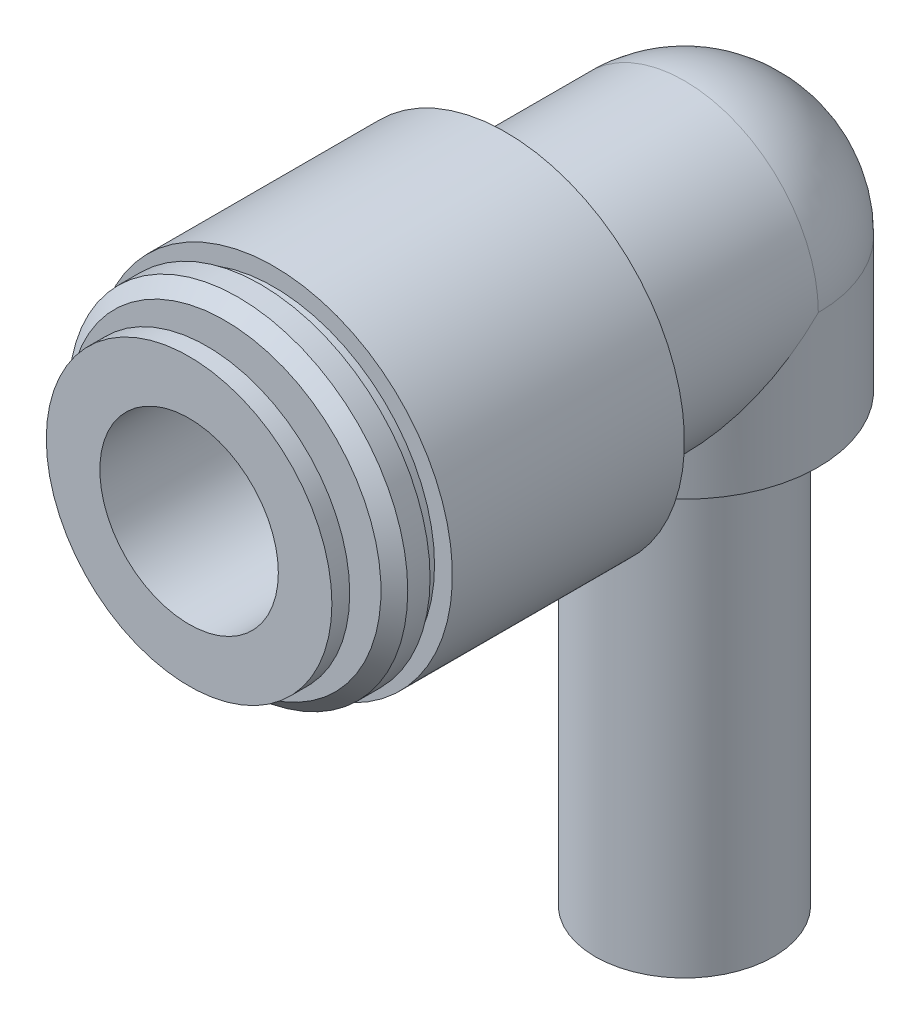
SolidWorks part; units mm, degrees
ref_plane "Спереди" through (0, 0, 0) normal (0, 0, 1) x (1, 0, 0)
ref_plane "Сверху" through (0, 0, 0) normal (0, 1, 0) x (1, 0, 0)
ref_plane "Справа" through (0, 0, 0) normal (1, 0, 0) x (0, 0, -1)
sketch "Эскиз1" plane through (0, 0, 0) normal (0, 1, 0) x (1, 0, 0)
  circle A0 centre (0, 0) radius 5
  circle A1 centre (0, 0) radius 4
  dimension "D1" = 8
  dimension "D2" = 10
extrude "Бобышка-Вытянуть1" add sketch "Эскиз1" along normal blind 25
sketch "Эскиз2" plane through (0, 0, 0) normal (0, 0, 1) x (1, 0, 0)
  line L0 (0, 25) -> (0, 40)
  line L1 (5, 25) -> (-5, 25) construction
  line L2 (0, 25) -> (7.5, 25)
  line L3 (7.5, 25) -> (7.5, 32.5)
  arc A0 (7.5, 32.5) -> (0, 40) centre (0, 32.5) ccw
revolve "Повернуть1" add sketch "Эскиз2" angle 360 about L0
sketch "Эскиз3" plane through (0, 0, 0) normal (0, 0, 1) x (1, 0, 0)
  circle A1 centre (0, 32.5) radius 7.5
extrude "Бобышка-Вытянуть2" add sketch "Эскиз3" along normal blind 10
sketch "Эскиз4" plane through (0, 0, 10) normal (0, 0, 1) x (1, 0, 0)
  circle A0 centre (0, 32.5) radius 10
extrude "Бобышка-Вытянуть3" add sketch "Эскиз4" along normal blind 13
sketch "Эскиз5" plane through (0, 0, 0) normal (1, 0, 0) x (0, 0, -1)
  line L9 (-26.75, 24.5) -> (-26.75, 26.5)
  line L11 (-27.75, 28.5) -> (-27.75, 24.5)
  line L13 (-27.75, 24.5) -> (-26.75, 24.5)
  line L15 (-25.75, 26.5) -> (-25.75, 23.75)
  line L16 (-25, 23) -> (-23.75, 23)
  line L17 (-25.75, 23.75) -> (-25, 23)
  line L18 (-23.75, 23) -> (-23.75, 23.5)
  line L19 (-23.75, 23.5) -> (-23, 23.5)
  line L20 (-23, 23.5) -> (-23, 28.5)
  line L21 (-27.75, 28.5) -> (-23, 28.5)
  line L22 (-26.75, 26.5) -> (-25.75, 26.5)
  line L23 (-23, 32.5) -> (-33.2854, 32.5) construction
  line L24 (-23, 42.5) -> (-23, 22.5) construction
  point P13 (-25.75, 23)
  dimension "D4" = 0.75
  dimension "D5" = 0.75
  dimension "D6" = 2
revolve "Повернуть3" add sketch "Эскиз5" angle 360 about L23
sketch "Эскиз6" plane through (0, 0, 27.75) normal (0, 0, 1) x (1, 0, 0)
  circle A0 centre (0, 32.5) radius 5
  dimension "D1" = 10
extrude "Вырез-Вытянуть1" cut sketch "Эскиз6" against normal blind 28
sketch3d "Трехмерный эскиз1"
  circle A1 centre (-51.3445, 36.7788, 165) radius 8.5 construction
  circle A2 centre (0, 32.5, 27.75) radius 5 construction
  spline S0 degree 3 poles (0, 32.5, 10) (6.4435, 31.963, 74.0243) (-60.2245, 37.5188, 124.7319) (-51.3445, 36.7788, 189.2) knots 0 0 0 0 1 1 1 1
  point P5 (-51.3445, 36.7788, 156.5)
  point P8 (0, 32.5, 32.75)
